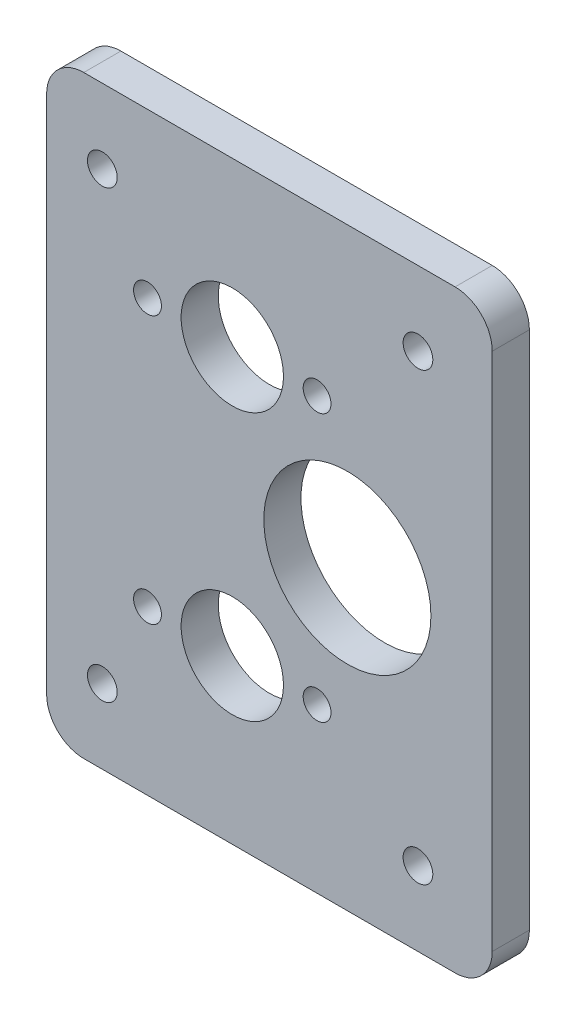
SolidWorks part; units mm, degrees
ref_plane "Front Plane" through (0, 0, 0) normal (0, 0, 1) x (1, 0, 0)
ref_plane "Top Plane" through (0, 0, 0) normal (0, 1, 0) x (1, 0, 0)
ref_plane "Right Plane" through (0, 0, 0) normal (1, 0, 0) x (0, 0, -1)
sketch "Sketch1" plane through (0, 0, 0) normal (0, 0, 1) x (1, 0, 0)
  line L0 (0, 0) -> (0, -45.72)
  line L1 (0, 0) -> (19.6773, -22.86)
  line L2 (-25.4, 27.94) -> (38.1, 27.94)
  line L3 (-31.75, 21.59) -> (-31.75, -67.31)
  line L4 (-25.4, -73.66) -> (38.1, -73.66)
  line L5 (44.45, 21.59) -> (44.45, -67.31)
  line L6 (0, -45.72) -> (19.6773, -22.86)
  circle A0 centre (0, 0) radius 14.5
  circle A1 centre (0, 0) radius 22.225
  circle A2 centre (0, -45.72) radius 22.15
  circle A3 centre (0, -45.72) radius 14.5
  circle A4 centre (14.5, 0) radius 2.3812
  circle A5 centre (-14.5, 0) radius 2.3813
  circle A6 centre (14.5, -45.72) radius 2.3812
  circle A7 centre (-14.5, -45.72) radius 2.3813
  circle A8 centre (19.6773, -22.86) radius 14.2875
  arc A9 (-31.75, -67.31) -> (-25.4, -73.66) centre (-25.4, -67.31) ccw
  circle A10 centre (0, -45.72) radius 8.75
  circle A11 centre (0, 0) radius 8.75
  arc A12 (38.1, -73.66) -> (44.45, -67.31) centre (38.1, -67.31) ccw
  arc A13 (38.1, 27.94) -> (44.45, 21.59) centre (38.1, 21.59) cw
  arc A14 (-25.4, 27.94) -> (-31.75, 21.59) centre (-25.4, 21.59) ccw
  point P0 (0, 0)
  point P16 (0, -22.86)
  dimension "D1" = 29
  dimension "D2" = 44.45
  dimension "D4" = 44.3
  dimension "D5" = 29
  dimension "D6" = 4.7625
  dimension "D7" = 4.7625
  dimension "D8" = 4.7625
  dimension "D9" = 4.7625
  dimension "D16" = 30.1625
  dimension "D17" = 17.5
  dimension "D18" = 17.5
  dimension "D20" = 28.575
  dimension "D21" = 6.35
  dimension "D3" = 45.72
  dimension "D10" = 31.75
  dimension "D11" = 50.8
  dimension "D12" = 50.8
  dimension "D13" = 44.45
  dimension "D14" = 30.1625
  dimension "D15" = 0
  dimension "D19" = 0
extrude "Boss-Extrude1" add sketch "Sketch1" along normal blind 6.35
sketch "Sketch2" plane through (0, 0, 6.35) normal (0, 0, 1) x (1, 0, 0)
  line L4 (38.1, 27.94) -> (-25.4, 27.94)
  line L5 (-31.75, 21.59) -> (-31.75, -67.31)
  line L6 (-25.4, -73.66) -> (38.1, -73.66)
  line L7 (44.45, -67.31) -> (44.45, 21.59)
  line L8 (38.1, 27.94) -> (-25.4, 27.94)
  line L9 (-31.75, 21.59) -> (-31.75, -67.31)
  line L10 (-25.4, -73.66) -> (38.1, -73.66)
  line L11 (44.45, -67.31) -> (44.45, 21.59)
  arc A4 (-25.4, 27.94) -> (-31.75, 21.59) centre (-25.4, 21.59) ccw
  arc A5 (-31.75, -67.31) -> (-25.4, -73.66) centre (-25.4, -67.31) ccw
  arc A6 (38.1, -73.66) -> (44.45, -67.31) centre (38.1, -67.31) ccw
  arc A7 (44.45, 21.59) -> (38.1, 27.94) centre (38.1, 21.59) ccw
  arc A8 (-25.4, 27.94) -> (-31.75, 21.59) centre (-25.4, 21.59) ccw
  arc A9 (-31.75, -67.31) -> (-25.4, -73.66) centre (-25.4, -67.31) ccw
  arc A10 (38.1, -73.66) -> (44.45, -67.31) centre (38.1, -67.31) ccw
  arc A11 (44.45, 21.59) -> (38.1, 27.94) centre (38.1, 21.59) ccw
  circle A16 centre (-22.225, 15.24) radius 2.54
  circle A17 centre (31.75, 15.24) radius 2.54
  circle A18 centre (31.75, -60.96) radius 2.54
  circle A19 centre (-22.225, -60.96) radius 2.54
  dimension "D2" = 5.08
  dimension "D5" = 5.08
  dimension "D6" = 5.08
  dimension "D9" = 12.7
  dimension "D11" = 5.08
  dimension "D3" = 12.7
  dimension "D4" = 9.525
  dimension "D7" = 12.7
  dimension "D8" = 12.7
  dimension "D10" = 12.7
  dimension "D12" = 12.7
  dimension "D13" = 9.525
  dimension "D1" = 0
extrude "Cut-Extrude1" cut sketch "Sketch2" against normal up to surface (6.35 mm away) contours A16 | A17 | A18 | A19 up to face at (8.75, -45.72, 0)
